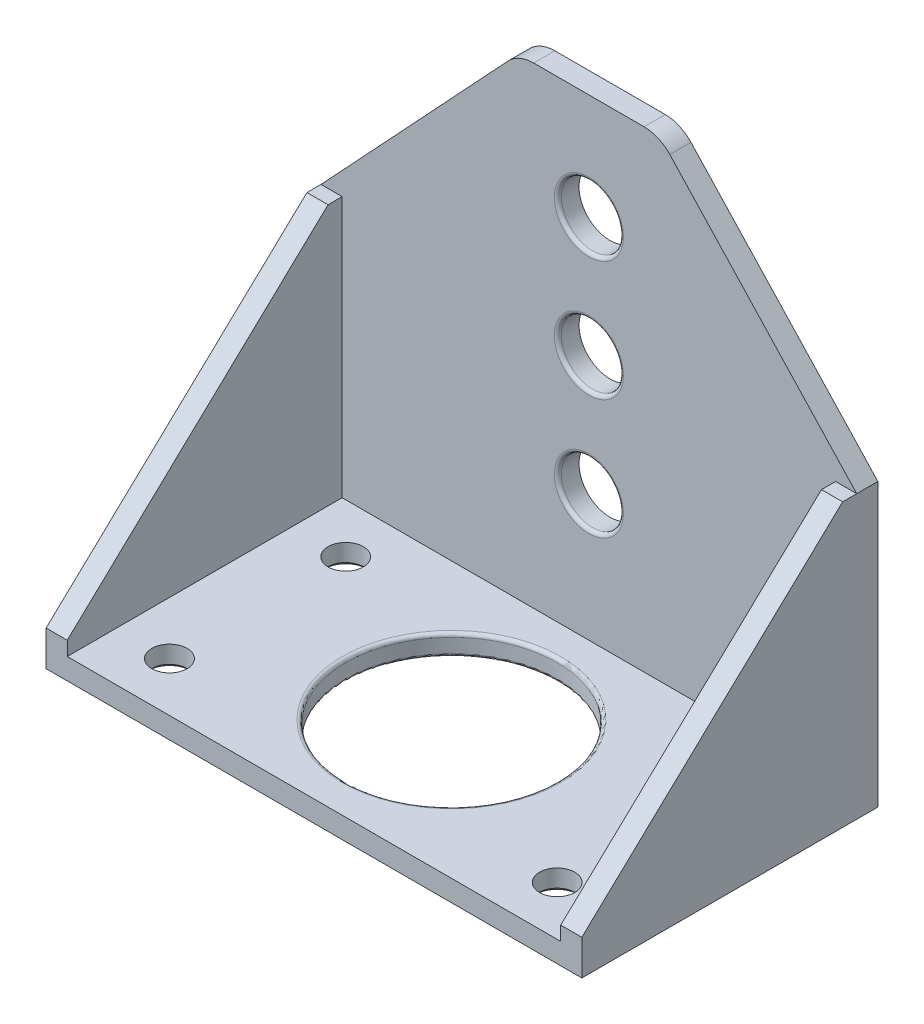
SolidWorks part; units mm, degrees
ref_plane "前视基准面" through (0, 0, 0) normal (0, 0, 1) x (1, 0, 0)
ref_plane "上视基准面" through (0, 0, 0) normal (0, 1, 0) x (1, 0, 0)
ref_plane "右视基准面" through (0, 0, 0) normal (1, 0, 0) x (0, 0, -1)
other "Configuration Table"
sketch "草图1" plane through (0, 0, 0) normal (0, 0, 1) x (1, 0, 0)
  line L0 (0, 0) -> (76, 0)
  line L1 (76, 0) -> (76, 40)
  line L2 (48, 70) -> (28, 70)
  line L3 (0, 40) -> (0, 0)
  line L4 (48, 70) -> (76, 40)
  line L5 (28, 70) -> (48, 70)
  line L7 (28, 70) -> (0, 40)
  dimension "D1" = 20
  dimension "D2" = 76
  dimension "D3" = 28
  dimension "D4" = 30
  dimension "D5" = 40
extrude "凸台-拉伸1" add sketch "草图1" along normal blind 3 contours L2 L7 L3 L0 L1 L4
sketch "草图2" plane through (0, 0, 3) normal (0, 0, 1) x (1, 0, 0)
  line L0 (76, 0) -> (76, 3)
  line L1 (76, 0) -> (76, 40) construction
  line L2 (76, 3) -> (0, 3)
  line L3 (0, 40) -> (0, 0) construction
  line L4 (0, 3) -> (0, 0)
  line L5 (0, 0) -> (76, 0)
extrude "凸台-拉伸2" add sketch "草图2" along normal blind 39
sketch "草图3" plane through (0, 3, 0) normal (0, 1, 0) x (1, 0, 0)
  line L0 (38, -42) -> (2, -42)
  line L1 (76, -42) -> (0, -42) construction
  line L2 (2, -42) -> (2, -3)
  line L3 (28, -3) -> (0, -3) construction
  line L4 (2, -3) -> (74, -3)
  line L5 (48, -3) -> (76, -3) construction
  line L6 (74, -3) -> (74, -42)
  line L7 (74, -42) -> (38, -42)
  line L8 (38, -42) -> (38, -3)
  line L10 (10.5, -10) -> (65.5, -10)
  line L11 (10.5, -10) -> (10.5, -35)
  line L12 (10.5, -35) -> (65.5, -35)
  line L13 (65.5, -10) -> (65.5, -35)
  line L14 (10.5, -10) -> (65.5, -35) construction
  line L15 (10.5, -35) -> (65.5, -10) construction
  circle A0 centre (65.5, -10) radius 3
  circle A1 centre (65.5, -35) radius 3
  circle A2 centre (10.5, -10) radius 3
  circle A3 centre (10.5, -35) radius 3
  point P10 (38, -22.5)
  dimension "D1" = 55
  dimension "D2" = 25
sketch "草图7" plane through (0, 0, 3) normal (0, 0, 1) x (1, 0, 0)
  line L0 (38, 70) -> (38, 3)
  line L1 (48, 70) -> (28, 70) construction
  line L2 (76, 3) -> (0, 3) construction
  circle A0 centre (38, 55) radius 4.4
  circle A1 centre (38, 38) radius 4.4
  circle A2 centre (38, 21) radius 4.4
  dimension "D1" = 15
  dimension "D2" = 17
  dimension "D3" = 17
  dimension "D4" = 8.8
  dimension "D5" = 8.8
  dimension "D6" = 8.8
extrude "切除-拉伸1" cut sketch "草图7" against normal blind 52 contours L0 A0 | L0 A0 | L0 A1 | L0 A1 | L0 A2 | L0 A2
sketch "草图8" plane through (0, 3, 0) normal (0, 1, 0) x (1, 0, 0)
  line L0 (76, -22.5) -> (0, -22.5)
  line L1 (76, -42) -> (76, -3) construction
  line L2 (0, -42) -> (0, -3) construction
  circle A0 centre (38, -22.5) radius 15
  dimension "D1" = 30
extrude "切除-拉伸2" cut sketch "草图8" against normal blind 52 contours L0 A0 | L0 A0
sketch "草图10" plane through (0, 0, 0) normal (-1, 0, 0) x (0, 0, 1)
  line L0 (3, 40) -> (5, 40)
  line L1 (42, 3) -> (42, 5)
  line L2 (42, 5) -> (5, 40)
  line L3 (3, 40) -> (3, 3)
  line L4 (3, 3) -> (42, 3)
extrude "凸台-拉伸3" add sketch "草图10" against normal blind 3
ref_plane "基准面1" through (38, 0, 0) normal (1, 0, 0) x (0, 0, -1)
mirror "镜向1" about plane through (38, 0, 0) normal (1, 0, 0) of "凸台-拉伸3"
hole_wizard "M6 螺纹孔2" positions "草图13" profile "草图14" tap size "M6" standard "GB" end condition through all
sketch "草图13" plane through (0, 0, 0) normal (0, -1, 0) x (-1, 0, 0)
  point P0 (-65.5, -10)
  point P3 (-10.5, -10)
  point P6 (-10.5, -35)
  point P9 (-65.5, -35)
sketch "草图14" plane through (65.5, 0, 10) normal (1, 0, 0) x (0, 0, -1)
  line L0 (0, 0) -> (0, 70)
  line L1 (0, 70) -> (2.5, 70)
  line L2 (2.5, 70) -> (2.5, 0.525)
  line L3 (2.5, 0.525) -> (3.025, 0)
  line L5 (3.025, 0) -> (0, 0)
  line L6 (-2.5, 0.525) -> (-3.025, 0) construction
  line L11 (0, -6.35) -> (0, 107.95) construction
  dimension "通孔螺纹孔钻头直径" = 5
  dimension "通孔螺纹孔钻头深度" = 70
  dimension "近端锥形沉头孔直径" = 6.05
  dimension "近端锥形沉头孔角度" = 90
cosmetic thread "孔螺蚊线5" parameters "D2"=6
cosmetic thread "孔螺蚊线6" parameters "D2"=6
cosmetic thread "孔螺蚊线7" parameters "D2"=6
cosmetic thread "孔螺蚊线8" parameters "D2"=6
fillet "圆角4" radius 5 2 edges at (48, 70, 1.5) (28, 70, 1.5)
fillet "圆角5" radius 0.5 5 edges at (38, 0, 37.5) (23, 3, 22.5) (42.4, 55, 3) (42.4, 21, 3) (42.4, 38, 3)
sketch "草图15" plane through (0, 0, 3) normal (0, 0, 1) x (1, 0, 0)
  line L0 (76, 5) -> (76, 40) construction
  line L1 (0, 40) -> (76, 40)
  line L2 (0, 40) -> (0, 71.4553)
  line L3 (0, 71.4553) -> (76, 71.4553)
  line L4 (76, 40) -> (76, 71.4553)
extrude "切除-拉伸3" [suppressed] cut sketch "草图15" against normal blind 21
